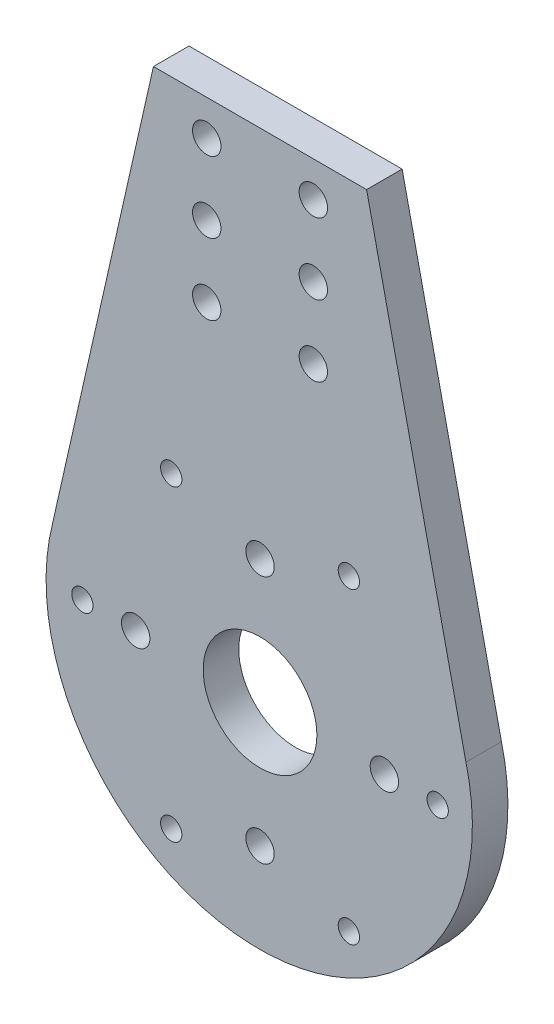
SolidWorks part; units mm, degrees
material "Acrylic (Medium-high impact)"
ref_plane "Front Plane" through (0, 0, 0) normal (0, 0, 1) x (1, 0, 0)
ref_plane "Top Plane" through (0, 0, 0) normal (0, 1, 0) x (1, 0, 0)
ref_plane "Right Plane" through (0, 0, 0) normal (1, 0, 0) x (0, 0, -1)
sketch "Sketch1" plane through (0, 0, 0) normal (0, 0, 1) x (1, 0, 0)
  line L0 (0, 0) -> (0, 102.4347) construction
  line L3 (-15, 70) -> (15, 70)
  line L6 (-53.7823, 0) -> (57.6054, 0) construction
  line L7 (57.6054, 0) -> (0, 0) construction
  line L8 (0, 0) -> (28.5913, 49.5216) construction
  line L9 (28.5913, 49.5216) -> (0, 0) construction
  line L10 (0, 0) -> (25.2625, -43.7558) construction
  line L11 (25.2625, -43.7558) -> (-22.2856, 38.5998) construction
  line L12 (-22.2856, 38.5998) -> (0, 0) construction
  line L13 (0, 0) -> (-22.4095, -38.8144) construction
  line L14 (-15, 70) -> (-29.2031, 7.195)
  line L15 (15, 70) -> (28.9776, 7.195)
  line L16 (0, 0) -> (0, -37.4282) construction
  circle A1 centre (0, 0) radius 17.5 construction
  circle A4 centre (0, 0) radius 25 construction
  circle A5 centre (25, 0) radius 1.5
  circle A6 centre (12.5, 21.6506) radius 1.5
  circle A7 centre (-12.5, 21.6506) radius 1.5
  circle A8 centre (-25, 0) radius 1.5
  circle A9 centre (-12.5, -21.6506) radius 1.5
  circle A10 centre (12.5, -21.6506) radius 1.5
  circle A12 centre (7.5, 65) radius 2
  circle A13 centre (7.5, 55) radius 2
  circle A14 centre (-7.5, 65) radius 2
  circle A15 centre (-7.5, 55) radius 2
  circle A18 centre (0, 0) radius 8
  circle A19 centre (0, 17.5) radius 2
  circle A20 centre (17.5, 0) radius 2
  circle A21 centre (0, -17.5) radius 2
  circle A22 centre (-17.5, 0) radius 2
  circle A23 centre (-7.5, 45) radius 2
  circle A24 centre (7.5, 45) radius 2
  circle A25 centre (-0.1127, -0.1365) radius 30
  arc A26 (28.9776, 7.195) -> (-29.2031, 7.195) centre (-0.1127, -0.1365) ccw
  dimension "D1" = 30
  dimension "D2" = 35
  dimension "D6" = 60
  dimension "D8" = 7.5
  dimension "D12" = 10
  dimension "D4" = 15
  dimension "D5" = 70
  dimension "D7" = 60
  dimension "D9" = 7.5
  dimension "D10" = 7.5
  dimension "D11" = 7.5
  dimension "D13" = 10
  dimension "D14" = 5
  dimension "D15" = 10
  dimension "D17" = 5
  dimension "D18" = 10
extrude "Boss-Extrude1" add sketch "Sketch1" along normal blind 5
